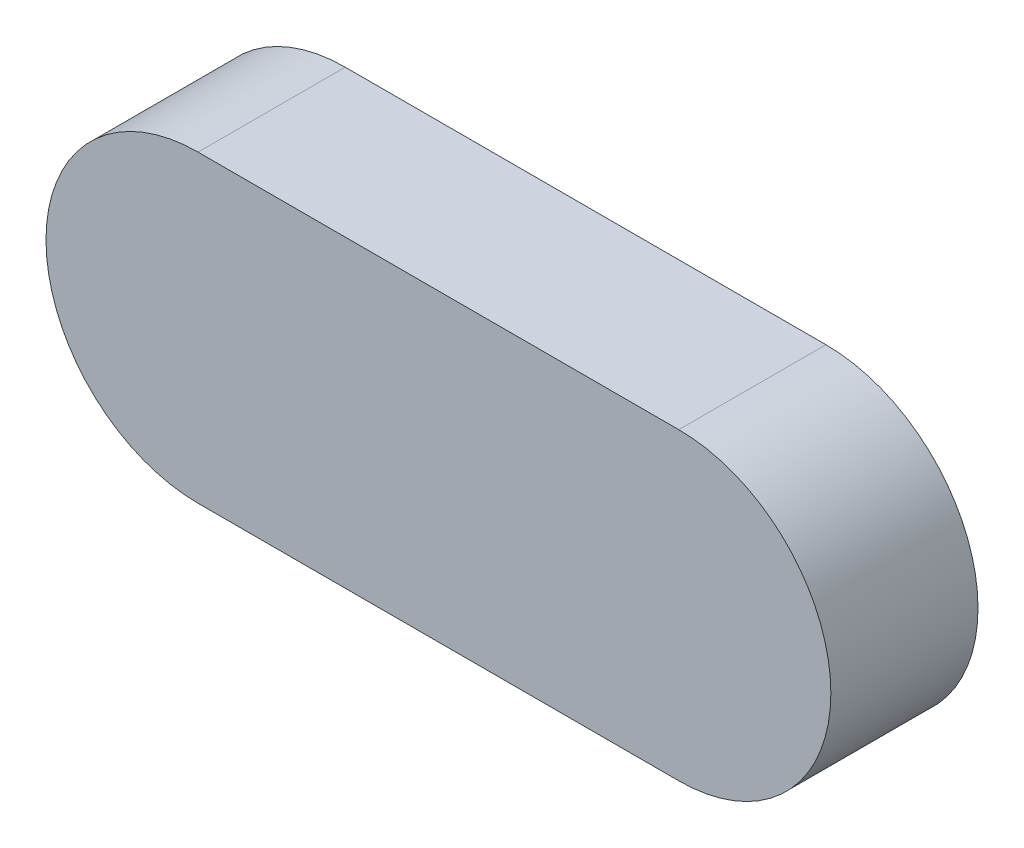
SolidWorks part; units mm, degrees
ref_plane "Front Plane" through (0, 0, 0) normal (0, 0, 1) x (1, 0, 0)
ref_plane "Top Plane" through (0, 0, 0) normal (0, 1, 0) x (1, 0, 0)
ref_plane "Right Plane" through (0, 0, 0) normal (1, 0, 0) x (0, 0, -1)
sketch "Sketch1" plane through (0, 0, 0) normal (0, 0, 1) x (1, 0, 0)
  line L0 (0, 0) -> (24.5, 0) construction
  line L1 (0, 7.75) -> (24.5, 7.75)
  line L2 (0, -7.75) -> (24.5, -7.75)
  arc A0 (0, 7.75) -> (0, -7.75) centre (0, 0) ccw
  arc A1 (24.5, -7.75) -> (24.5, 7.75) centre (24.5, 0) ccw
  point P3 (12.25, 0)
  dimension "D2" = 7.75
  dimension "D1" = 24.5
extrude "Boss-Extrude1" add sketch "Sketch1" along normal blind 7.5
